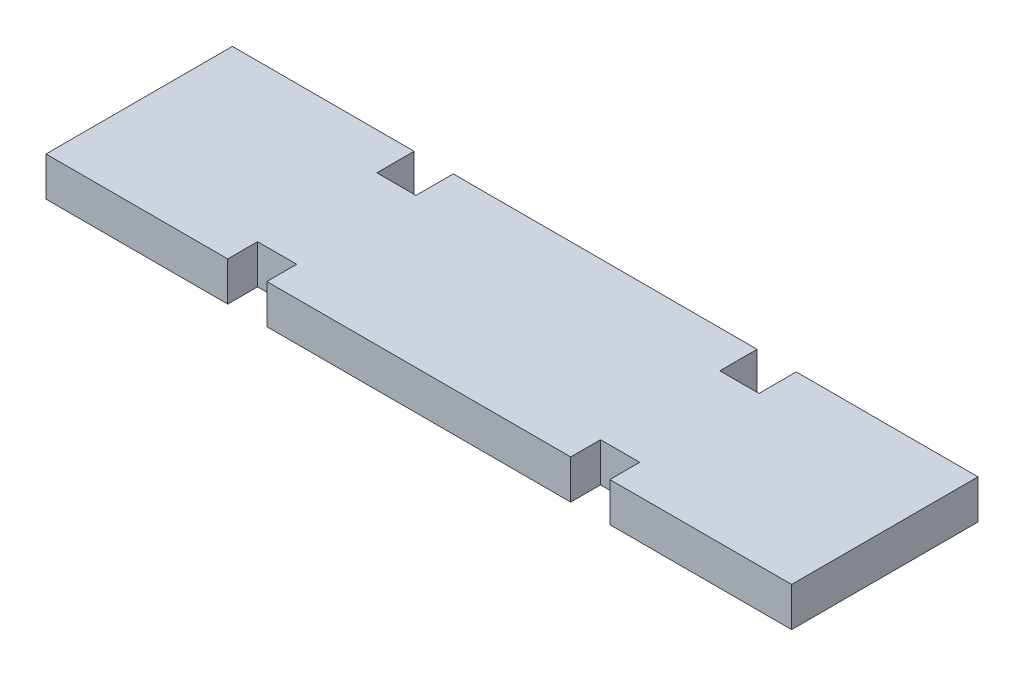
SolidWorks part; units mm, degrees
ref_plane "Front Plane" through (0, 0, 0) normal (0, 0, 1) x (1, 0, 0)
ref_plane "Top Plane" through (0, 0, 0) normal (0, 1, 0) x (1, 0, 0)
ref_plane "Right Plane" through (0, 0, 0) normal (1, 0, 0) x (0, 0, -1)
sketch "Sketch1" plane through (0, 0, 0) normal (0, 1, 0) x (1, 0, 0)
  line L1 (-61.4444, 32.873) -> (40.1556, 32.873)
  line L2 (-61.4444, 32.873) -> (-61.4444, 7.473)
  line L3 (-61.4444, 7.473) -> (40.1556, 7.473)
  line L4 (40.1556, 32.873) -> (40.1556, 7.473)
  dimension "D1" = 101.6
  dimension "D2" = 25.4
extrude "Boss-Extrude1" add sketch "Sketch1" along normal blind 5.334
sketch "Sketch2" plane through (0, 5.334, 0) normal (0, 1, 0) x (1, 0, 0)
  line L0 (-10.6444, 32.873) -> (-10.6444, 7.473) construction
  line L1 (40.1556, 32.873) -> (-61.4444, 32.873) construction
  line L2 (-61.4444, 7.473) -> (40.1556, 7.473) construction
  line L3 (-36.6794, 7.473) -> (-36.6794, 11.537)
  line L4 (10.0566, 32.873) -> (15.3906, 32.873)
  line L5 (10.0566, 32.873) -> (10.0566, 27.793)
  line L6 (10.0566, 27.793) -> (15.3906, 27.793)
  line L7 (15.3906, 32.873) -> (15.3906, 27.793)
  line L8 (10.0566, 7.473) -> (15.3906, 7.473)
  line L9 (10.0566, 7.473) -> (10.0566, 11.537)
  line L10 (10.0566, 11.537) -> (15.3906, 11.537)
  line L11 (15.3906, 7.473) -> (15.3906, 11.537)
  line L12 (-31.3454, 11.537) -> (-36.6794, 11.537)
  line L13 (-31.3454, 7.473) -> (-31.3454, 11.537)
  line L14 (-31.3454, 7.473) -> (-36.6794, 7.473)
  line L15 (-36.6794, 32.873) -> (-36.6794, 27.793)
  line L16 (-31.3454, 27.793) -> (-36.6794, 27.793)
  line L17 (-31.3454, 32.873) -> (-31.3454, 27.793)
  line L18 (-31.3454, 32.873) -> (-36.6794, 32.873)
  dimension "D1" = 20.701
  dimension "D2" = 5.334
  dimension "D3" = 5.08
  dimension "D4" = 4.064
extrude "Cut-Extrude1" cut sketch "Sketch2" against normal through all
equation "\"MDF\"= .21in"
equation "\"Foamcore\"= .13in"
equation "\"Gmaterial\"= \"MDF\""
equation "\"D1@Boss-Extrude1\"=\"MDF\""
equation "\"D2@Sketch2\"=\"MDF\""
